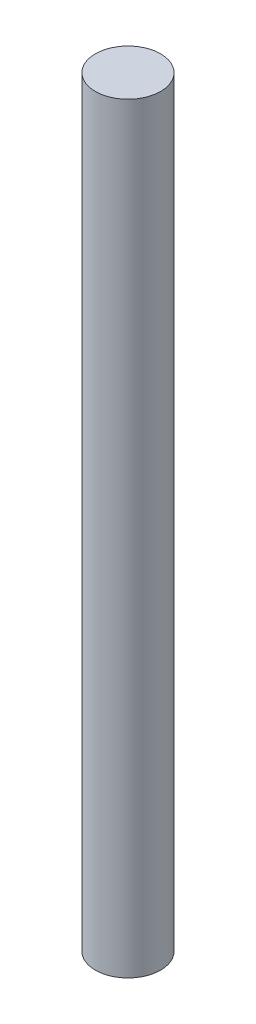
SolidWorks part; units mm, degrees
ref_plane "Front Plane" through (0, 0, 0) normal (0, 0, 1) x (1, 0, 0)
ref_plane "Top Plane" through (0, 0, 0) normal (0, 1, 0) x (1, 0, 0)
ref_plane "Right Plane" through (0, 0, 0) normal (1, 0, 0) x (0, 0, -1)
sketch "Sketch1" plane through (0, 0, 0) normal (0, 1, 0) x (1, 0, 0)
  circle A0 centre (0, 0) radius 9
  dimension "D1" = 18
extrude "Boss-Extrude1" add sketch "Sketch1" along normal blind 210
